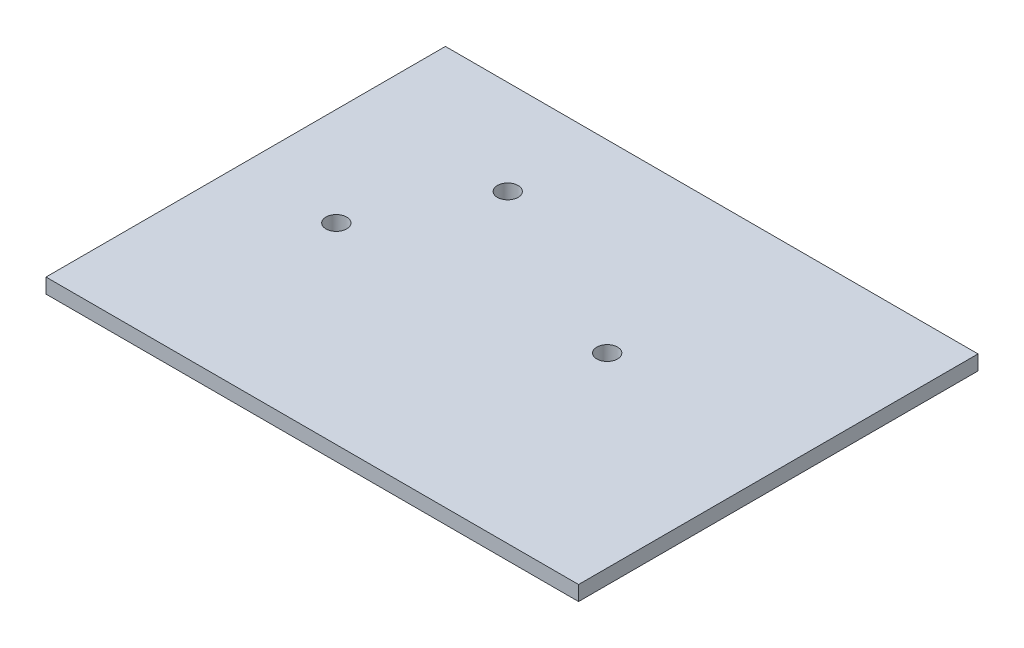
SolidWorks part; units mm, degrees
ref_plane "Front Plane" through (0, 0, 0) normal (0, 0, 1) x (1, 0, 0)
ref_plane "Top Plane" through (0, 0, 0) normal (0, 1, 0) x (1, 0, 0)
ref_plane "Right Plane" through (0, 0, 0) normal (1, 0, 0) x (0, 0, -1)
sketch "Sketch1" plane through (0, 0, 0) normal (0, 1, 0) x (1, 0, 0)
  line L1 (0, 0) -> (180, 0)
  line L2 (0, 0) -> (0, 135)
  line L3 (0, 135) -> (180, 135)
  line L4 (180, 0) -> (180, 135)
  dimension "D1" = 180
  dimension "D2" = 135
extrude "Boss-Extrude1" add sketch "Sketch1" along normal blind 5
sketch "Sketch5" plane through (0, 5, 0) normal (0, 1, 0) x (1, 0, 0)
  line L6 (0, 135) -> (0, 0)
  line L7 (0, 0) -> (180, 0)
  line L8 (180, 0) -> (180, 135)
  line L9 (180, 135) -> (0, 135)
  line L10 (0, 135) -> (0, 0)
  line L11 (0, 0) -> (180, 0)
  line L12 (180, 0) -> (180, 135)
  line L13 (180, 135) -> (0, 135)
  circle A0 centre (117.0856, 72.5848) radius 2.5 construction
  circle A1 centre (117.0856, 72.5848) radius 2.5 construction
  circle A2 centre (52.9711, 103.0861) radius 2.5 construction
  circle A3 centre (52.9711, 103.0861) radius 2.5 construction
  circle A5 centre (33.2371, 64.8817) radius 2.5 construction
  circle A7 centre (33.2371, 64.8817) radius 2.5 construction
  circle A8 centre (52.9711, 103.0861) radius 3.5
  circle A9 centre (117.0856, 72.5848) radius 3.5
  circle A10 centre (33.2371, 64.8817) radius 2.5 construction
  circle A11 centre (33.2371, 64.8817) radius 3.5
  dimension "D3" = 0
  dimension "D1" = 1
  dimension "D2" = 1
  dimension "D4" = 1
extrude "Cut-Extrude2" cut sketch "Sketch5" against normal through all flip side to cut
